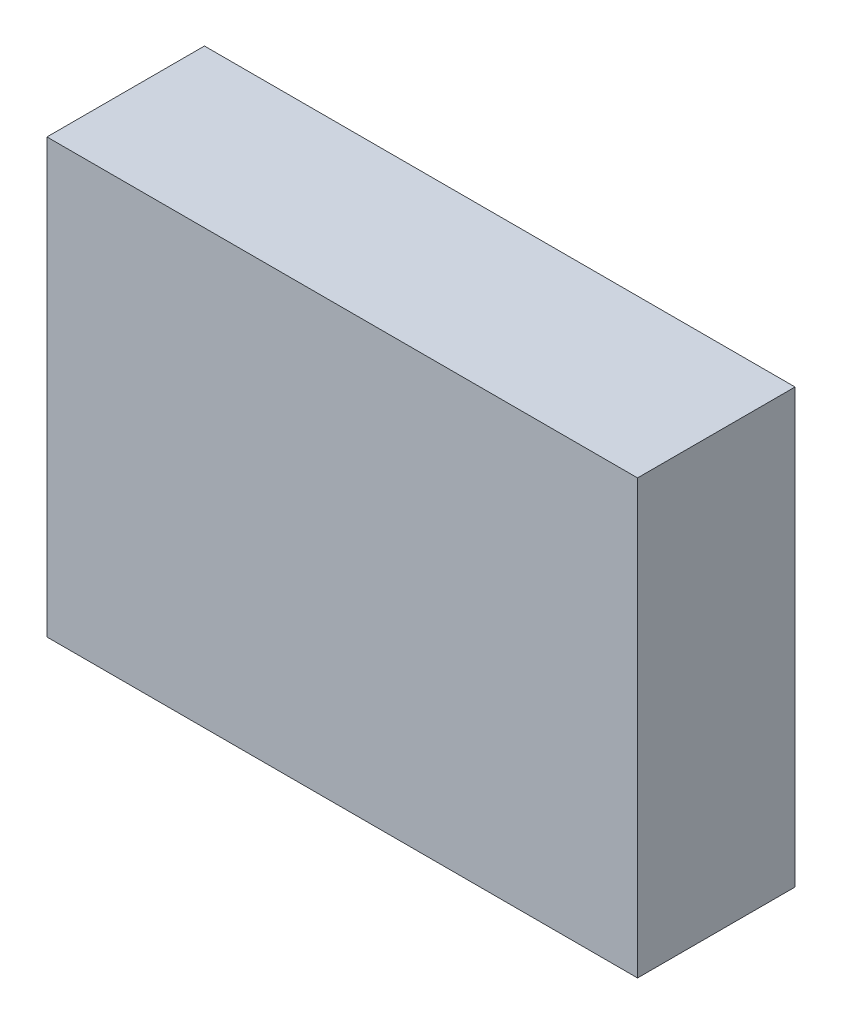
SolidWorks part; units mm, degrees
ref_plane "Front" through (0, 0, 0) normal (0, 0, 1) x (1, 0, 0)
ref_plane "Top" through (0, 0, 0) normal (0, 1, 0) x (1, 0, 0)
ref_plane "Right" through (0, 0, 0) normal (1, 0, 0) x (0, 0, -1)
sketch "Sketch1" plane through (0, 0, 0) normal (0, 1, 0) x (1, 0, 0)
  line L1 (-45, -12) -> (45, -12)
  line L2 (-45, -12) -> (-45, 12)
  line L3 (-45, 12) -> (45, 12)
  line L4 (45, -12) -> (45, 12)
  line L5 (-45, -12) -> (45, 12) construction
  line L6 (-45, 12) -> (45, -12) construction
  point P0 (0, 0)
  dimension "D1" = 24
  dimension "D2" = 90
extrude "Boss-Extrude1" add sketch "Sketch1" along normal blind 66
